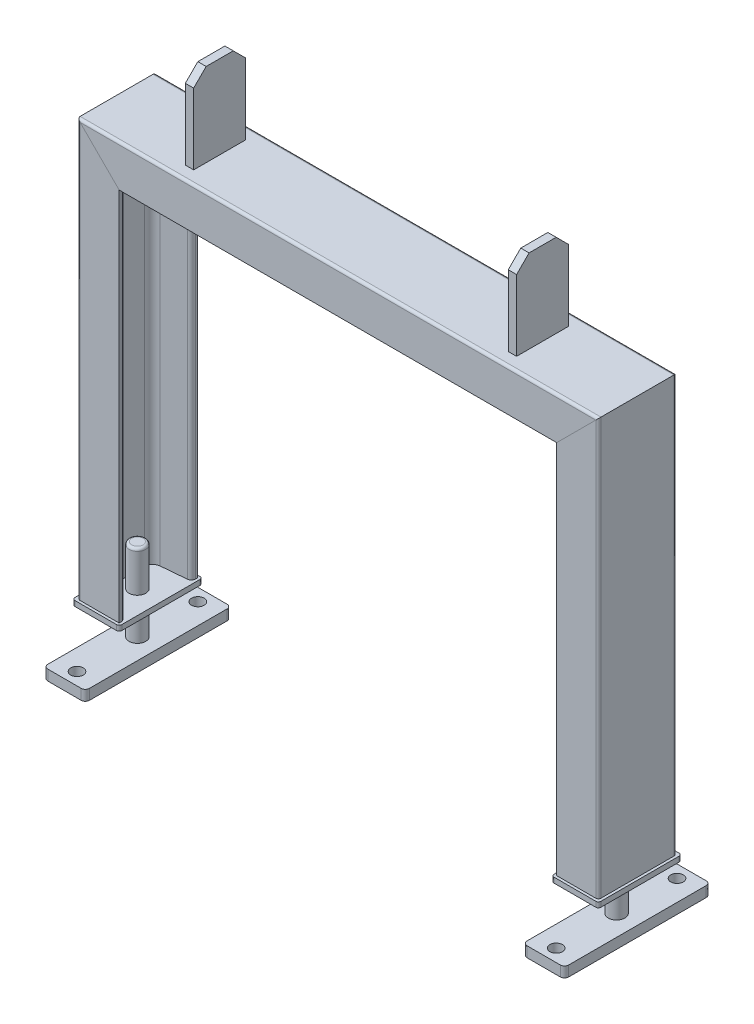
SolidWorks part; units mm, degrees
material "AISI 1015 Steel, Cold Drawn (SS)"
ref_plane "Front Plane" through (0, 0, 0) normal (0, 0, 1) x (1, 0, 0)
ref_plane "Top Plane" through (0, 0, 0) normal (0, 1, 0) x (1, 0, 0)
ref_plane "Right Plane" through (0, 0, 0) normal (1, 0, 0) x (0, 0, -1)
sketch "Sketch1" plane through (0, 0, 0) normal (0, 0, 1) x (1, 0, 0)
  line L0 (250, 0) -> (-250, 0)
  line L1 (-250, 0) -> (-250, -400)
  line L2 (250, 0) -> (250, -400)
  point P4 (0, 0)
  dimension "D1" = 500
  dimension "D2" = 400
other "Channel C 75 X 40 X 5.0(1)"
ref_plane "Plane1" through (-250, 0, -37.5) normal (0, -1, 0) x (1, 0, 0)
sketch "Sketch14" plane through (-250, 0, -37.5) normal (0, -1, 0) x (1, 0, 0)
  line L0 (40, 75) -> (0, 75)
  line L1 (40, 0) -> (0, 0)
  line L2 (0, 75) -> (0, 0)
  line L5 (0, 7) -> (22.5, 7) construction
  line L6 (40, 75) -> (40, 73.1964)
  line L7 (40, 0) -> (40, 1.8036)
  line L8 (5, 37.5) -> (0, 37.5) construction
  line L12 (5, 59.1383) -> (5, 15.8617)
  line L17 (12.3028, 67.1079) -> (36.3486, 69.2116)
  line L18 (12.3028, 7.8921) -> (36.3486, 5.7884)
  arc A0 (36.3486, 69.2116) -> (40, 73.1964) centre (36, 73.1964) ccw
  arc A1 (36.3486, 5.7884) -> (40, 1.8036) centre (36, 1.8036) cw
  arc A9 (5, 15.8617) -> (12.3028, 7.8921) centre (13, 15.8617) ccw
  arc A10 (5, 59.1383) -> (12.3028, 67.1079) centre (13, 59.1383) cw
  point P10 (20, 75)
  point P11 (20, 0)
  point P14 (0, 0)
  dimension "D4" = 17.5
  dimension "RI" = 8
  dimension "D2" = 5
  dimension "RA" = 4
  dimension "Depth" = 75
  dimension "BF" = 40
  dimension "TW" = 5
  dimension "TF" = 7
sketch "Sketch15" plane through (0, -400, 0) normal (0, -1, 0) x (1, 0, 0)
  line L0 (-252.5, 37.5) -> (-252.5, -37.5)
  line L1 (-250, 37.5) -> (-210, 37.5) construction
  line L3 (-250, -37.5) -> (-210, -37.5) construction
  line L5 (250, -37.5) -> (210, -37.5) construction
  line L6 (250, -37.5) -> (250, 37.5) construction
  line L7 (250, 37.5) -> (210, 37.5) construction
  line L8 (210, -37.5) -> (210, 37.5) construction
  line L9 (-250, -40) -> (-210, -40)
  line L10 (-207.5, 37.5) -> (-207.5, -37.5)
  line L11 (-250, 40) -> (-210, 40)
  line L12 (252.5, -37.5) -> (252.5, 37.5)
  line L13 (250, 40) -> (210, 40)
  line L14 (207.5, -37.5) -> (207.5, 37.5)
  line L15 (250, -40) -> (210, -40)
  line L16 (252.5, 40) -> (207.5, 40) construction
  line L17 (252.5, -40) -> (252.5, 40) construction
  line L18 (207.5, -40) -> (207.5, 40) construction
  line L19 (252.5, -40) -> (207.5, -40) construction
  line L20 (-252.5, 40) -> (-252.5, -40) construction
  line L21 (-252.5, -40) -> (-207.5, -40) construction
  line L22 (-207.5, 40) -> (-207.5, -40) construction
  line L23 (-252.5, 40) -> (-207.5, 40) construction
  line L24 (-250, 37.5) -> (-250, -37.5) construction
  line L25 (-210, 37.5) -> (-210, -37.5) construction
  line L26 (0, -55) -> (0, 55) construction
  line L27 (-210, 37.5) -> (-250, 37.5) construction
  line L28 (-210, 37.5) -> (-210, -37.5) construction
  line L29 (-210, -37.5) -> (-250, -37.5) construction
  line L30 (-250, 37.5) -> (-250, -37.5) construction
  line L31 (-210, 37.5) -> (-250, -37.5) construction
  line L32 (-210, -37.5) -> (-250, 37.5) construction
  arc A0 (250, 40) -> (252.5, 37.5) centre (250, 37.5) cw
  arc A1 (210, 40) -> (207.5, 37.5) centre (210, 37.5) ccw
  arc A2 (207.5, -37.5) -> (210, -40) centre (210, -37.5) ccw
  arc A3 (252.5, -37.5) -> (250, -40) centre (250, -37.5) cw
  arc A4 (-252.5, -37.5) -> (-250, -40) centre (-250, -37.5) ccw
  arc A5 (-210, -40) -> (-207.5, -37.5) centre (-210, -37.5) ccw
  arc A6 (-207.5, 37.5) -> (-210, 40) centre (-210, 37.5) ccw
  arc A7 (-250, 40) -> (-252.5, 37.5) centre (-250, 37.5) ccw
  circle A8 centre (-230, 0) radius 8
  circle A9 centre (230, 0) radius 8
  point P44 (-230, 0)
  dimension "D3" = 2.5
  dimension "D4" = 2.5
  dimension "D5" = 2.5
  dimension "D6" = 2.5
  dimension "D7" = 2.5
  dimension "D8" = 2.5
  dimension "D9" = 2.5
  dimension "D10" = 2.5
  dimension "D11" = 16
  dimension "D1" = 2.5
  dimension "D2" = 2.5
extrude "Boss-Extrude1" add sketch "Sketch15" along normal blind 5 separate body
fillet "Fillet1" radius 2.5 2 edges at (-250, -200, -37.5) (-250, -200, 37.5)
fillet "Fillet2" radius 2.5 2 edges at (0, 0, -37.5) (0, 0, 37.5)
fillet "Fillet3" radius 2.5 2 edges at (250, -200, -37.5) (250, -200, 37.5)
sketch "Sketch16" plane through (0, 0, 0) normal (0, 1, 0) x (1, 0, 0)
  line L0 (155, 0) -> (-155, 0)
  line L1 (0, -55) -> (0, 55) construction
  line L2 (-159, -25) -> (-151, -25)
  line L3 (-159, -25) -> (-159, 25)
  line L4 (-159, 25) -> (-151, 25)
  line L5 (-151, -25) -> (-151, 25)
  line L6 (-159, -25) -> (-151, 25) construction
  line L7 (-159, 25) -> (-151, -25) construction
  line L8 (159, 25) -> (151, -25) construction
  line L9 (159, -25) -> (151, 25) construction
  line L10 (151, -25) -> (151, 25)
  line L11 (159, 25) -> (151, 25)
  line L12 (159, -25) -> (159, 25)
  line L13 (159, -25) -> (151, -25)
  point P14 (0, 0)
  dimension "D1" = 8
  dimension "D2" = 50
  dimension "D3" = 151
extrude "Boss-Extrude2" add sketch "Sketch16" along normal blind 80 separate body
chamfer "Chamfer1" distance 12 2 edges at (-155, 80, -25) (-155, 80, 25)
chamfer "Chamfer2" distance 12 angle 45 2 edges at (155, 80, -25) (155, 80, 25)
sketch "Sketch17" plane through (0, -405, 0) normal (0, -1, 0) x (1, 0, 0)
  line L0 (0, -55) -> (0, 55) construction
  circle A0 centre (-230, 0) radius 8
  circle A1 centre (230, 0) radius 8
  dimension "D1" = 16
extrude "Boss-Extrude3" add sketch "Sketch17" along normal blind 35 and the other way blind 44 separate body
fillet "Fillet6" radius 2.5 1 edges at (-222, -361, 0)
fillet "Fillet7" radius 2.5 1 edges at (222, -361, 0)
sketch "Sketch18" plane through (0, -440, 0) normal (0, -1, 0) x (1, 0, 0)
  line L0 (-230, -58) -> (-230, 58) construction
  line L1 (-246, -70) -> (-214, -70)
  line L2 (-250, -66) -> (-250, 66)
  line L3 (-246, 70) -> (-214, 70)
  line L4 (-210, -66) -> (-210, 66)
  line L5 (-246, -66) -> (-214, 66) construction
  line L6 (-246, 66) -> (-214, -66) construction
  line L7 (0, -55) -> (0, 55) construction
  line L8 (246, 66) -> (214, -66) construction
  line L9 (246, -66) -> (214, 66) construction
  line L10 (230, -58) -> (230, 58) construction
  line L11 (210, -66) -> (210, 66)
  line L12 (246, 70) -> (214, 70)
  line L13 (250, -66) -> (250, 66)
  line L14 (246, -70) -> (214, -70)
  arc A0 (-250, -66) -> (-246, -70) centre (-246, -66) ccw
  arc A1 (-214, -70) -> (-210, -66) centre (-214, -66) ccw
  arc A2 (-214, 70) -> (-210, 66) centre (-214, 66) cw
  arc A3 (-246, 70) -> (-250, 66) centre (-246, 66) ccw
  circle A4 centre (-230, 58) radius 6
  circle A5 centre (-230, -58) radius 6
  circle A6 centre (230, -58) radius 6
  circle A7 centre (230, 58) radius 6
  arc A8 (246, 70) -> (250, 66) centre (246, 66) cw
  arc A9 (214, 70) -> (210, 66) centre (214, 66) ccw
  arc A10 (214, -70) -> (210, -66) centre (214, -66) cw
  arc A11 (250, -66) -> (246, -70) centre (246, -66) cw
  point P0 (-230, 0)
  point P25 (-230, 0)
  point P37 (230, 0)
  dimension "D2" = 4
  dimension "D3" = 4
  dimension "D1" = 4
  dimension "D4" = 4
  dimension "D8" = 12
  dimension "D5" = 140
  dimension "D6" = 40
  dimension "D7" = 116
extrude "Boss-Extrude4" add sketch "Sketch18" along normal blind 10 separate body
